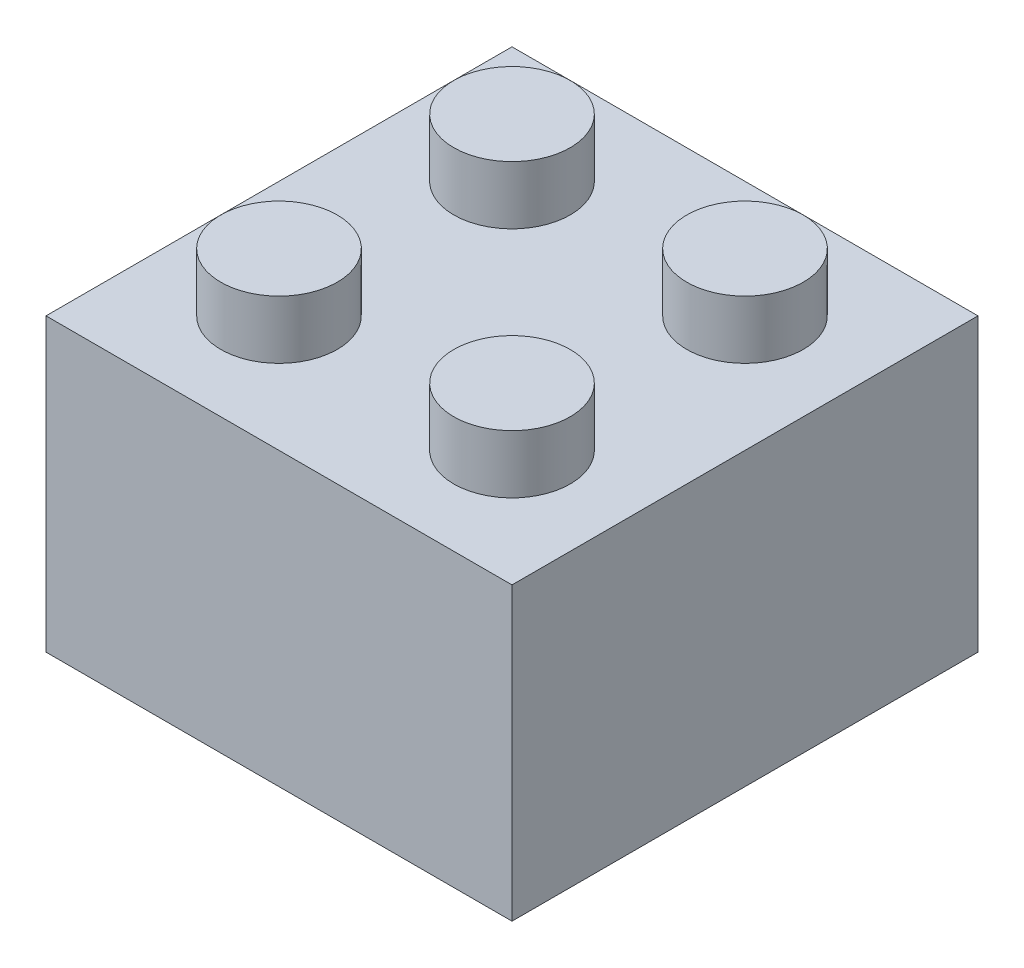
SolidWorks part; units mm, degrees
ref_plane "Front Plane" through (0, 0, 0) normal (0, 0, 1) x (1, 0, 0)
ref_plane "Top Plane" through (0, 0, 0) normal (0, 1, 0) x (1, 0, 0)
ref_plane "Right Plane" through (0, 0, 0) normal (1, 0, 0) x (0, 0, -1)
sketch "Sketch1" plane through (0, 0, 0) normal (0, 1, 0) x (1, 0, 0)
  line L1 (8, -8) -> (-8, -8)
  line L2 (8, -8) -> (8, 8)
  line L3 (8, 8) -> (-8, 8)
  line L4 (-8, -8) -> (-8, 8)
  line L5 (8, -8) -> (-8, 8) construction
  line L6 (8, 8) -> (-8, -8) construction
  point P0 (0, 0)
  dimension "D1" = 16
  dimension "D2" = 16
extrude "Boss-Extrude1" add sketch "Sketch1" along normal blind 10
sketch "Sketch2" plane through (0, 10, 0) normal (0, 1, 0) x (1, 0, 0)
  line L0 (0, 7.6616) -> (0, 0) construction
  line L1 (0, 0) -> (7.8224, 0) construction
  line L2 (-8, 8) -> (-8, -8) construction
  line L3 (8, 8) -> (-8, 8) construction
  circle A0 centre (-4, 4) radius 2
  circle A1 centre (4, 4) radius 2
  circle A2 centre (4, -4) radius 2
  circle A3 centre (-4, -4) radius 2
  dimension "D1" = 4
  dimension "D2" = 4
  dimension "D3" = 4
extrude "Boss-Extrude2" add sketch "Sketch2" along normal blind 2
shell "Shell2" thickness 1
sketch "Sketch3" plane through (0, 9, 0) normal (0, -1, 0) x (1, 0, 0)
  circle A0 centre (0, 0) radius 2.7
  circle A1 centre (0, 0) radius 1.7
  dimension "D1" = 3.4
  dimension "D2" = 5.4
extrude "Boss-Extrude3" add sketch "Sketch3" along normal blind 9
